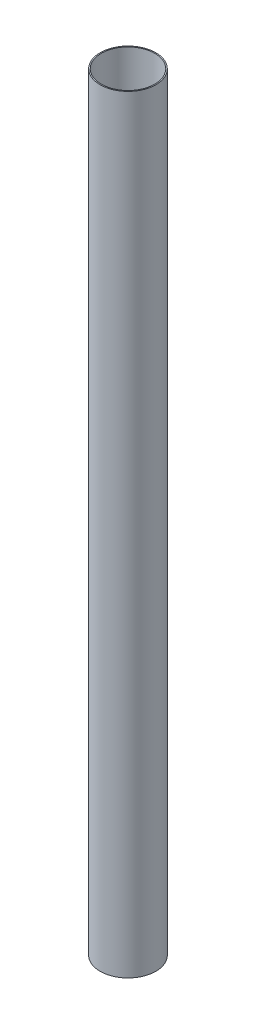
SolidWorks part; units mm, degrees
material "7075-T6 (SN)"
ref_plane "Front Plane" through (0, 0, 0) normal (0, 0, 1) x (1, 0, 0)
ref_plane "Top Plane" through (0, 0, 0) normal (0, 1, 0) x (1, 0, 0)
ref_plane "Right Plane" through (0, 0, 0) normal (1, 0, 0) x (0, 0, -1)
sketch "Sketch1" plane through (0, 0, 0) normal (0, 1, 0) x (1, 0, 0)
  circle A0 centre (0, 0) radius 49.53
  circle A1 centre (0, 0) radius 51.562
  dimension "D1" = 99.06
  dimension "D2" = 2.032
extrude "Boss-Extrude1" add sketch "Sketch1" along normal blind 1422.4
equation "\"CF_OD_A\"= 4.015in"
equation "\"CF_ID_A\"= 3.904in"
equation "\"KF_ID_A\"= 4.015in ' Kevlar airframe ID"
equation "\"CF_OD_C\"= 3.894in ' VERIFY Coupler OD"
equation "\"CF_ID_C\"= 3.783in ' VERIFY Coupler ID"
equation "\"KF_WALL\"= 0.0625in"
equation "\"AF_01\"=10in"
equation "\"AF_02\"=16in"
equation "\"AF_03\"=in"
equation "\"B_CF_OD\"=6.17in"
equation "\"B_CF_ID\"=6in"
equation "\"B_CF_WT\"=0.085in"
equation "\"B_Fin_Root\"=18in"
equation "\"Al_WALL\"=0.08in"
equation "\"AL_ID_A\"=3.9in"
equation "\"D1@Sketch1\"=\"AL_ID_A\""
equation "\"D2@Sketch1\"=\"Al_WALL\""
equation "\"D1@Boss-Extrude1\"=\"AF_03\""
